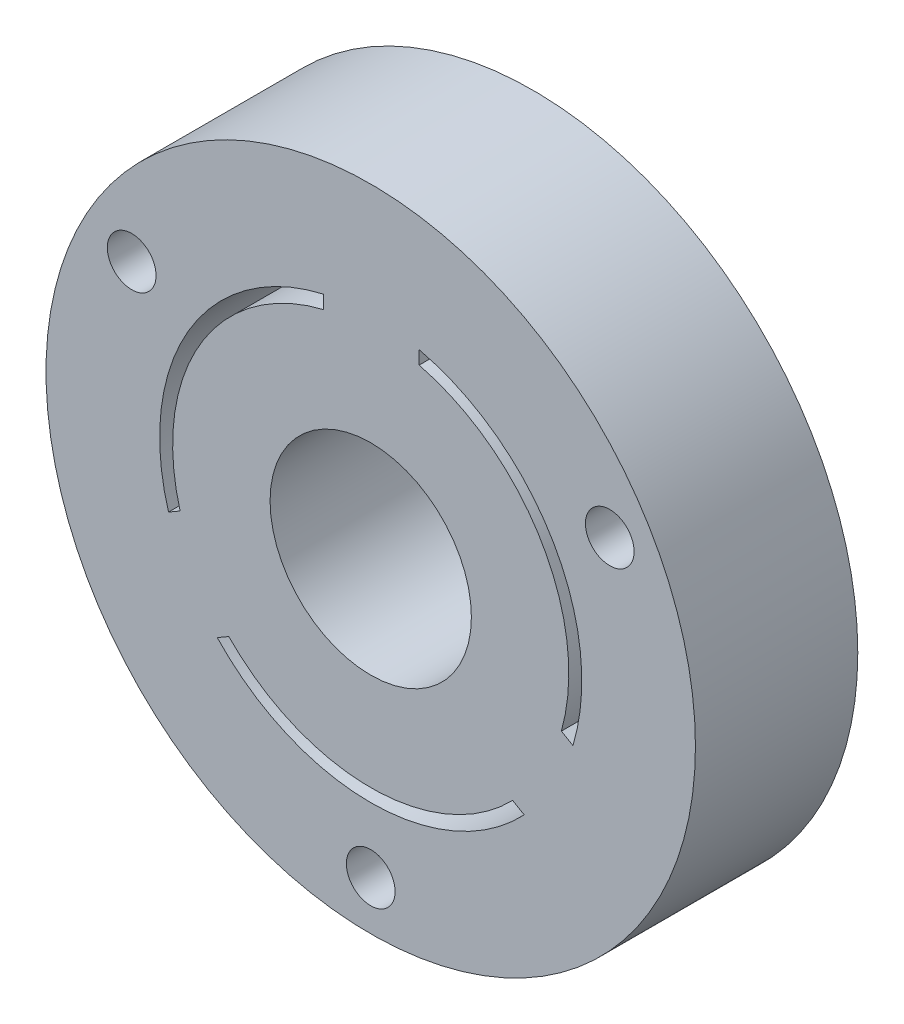
SolidWorks part; units mm, degrees
ref_plane "前视基准面" through (0, 0, 0) normal (0, 0, 1) x (1, 0, 0)
ref_plane "上视基准面" through (0, 0, 0) normal (0, 1, 0) x (1, 0, 0)
ref_plane "右视基准面" through (0, 0, 0) normal (1, 0, 0) x (0, 0, -1)
sketch "草图1" plane through (0, 0, 0) normal (0, 0, 1) x (1, 0, 0)
  line L0 (48.2965, 27.9249) -> (48.2965, 37.9249) construction
  line L1 (48.2965, 27.9249) -> (39.6362, 22.9249) construction
  line L2 (48.2965, 27.9249) -> (74.2772, 12.9249) construction
  line L3 (81.0732, 9.0013) -> (81.8232, 10.3003)
  line L7 (46.8483, 66.0915) -> (46.8483, 32.6388)
  line L11 (49.7879, 66.0915) -> (49.7879, 32.6388)
  line L12 (81.0732, 9.0013) -> (80.3232, 7.7022)
  line L13 (81.8232, 10.3003) -> (52.5654, 27.1923)
  line L14 (52.5654, 27.1923) -> (51.0654, 24.5942)
  line L15 (51.0654, 24.5942) -> (80.3232, 7.7022)
  line L16 (15.5198, 9.0013) -> (14.7698, 10.3003)
  line L17 (15.5198, 9.0013) -> (16.2698, 7.7022)
  line L18 (14.7698, 10.3003) -> (43.9274, 27.1345)
  line L19 (43.9274, 27.1345) -> (45.4274, 24.5364)
  line L20 (45.4274, 24.5364) -> (16.2698, 7.7022)
  line L21 (46.8483, 32.6388) -> (49.7879, 32.6388)
  line L22 (46.8483, 66.0915) -> (49.7879, 66.0915)
  circle A1 centre (48.2965, 27.9249) radius 3.1
  circle A2 centre (48.2965, 27.9249) radius 6.1
  circle A3 centre (48.2965, 27.9249) radius 10
  circle A4 centre (48.2965, 27.9249) radius 6.5
  dimension "D1" = 3
  dimension "D2" = 3.5
extrude "凸台-拉伸2" add sketch "草图1" along normal blind 5 contours A4 L7 A3 L18 | A4 L13 A3 L11 | A4 L20 A3 L15 | A4 L18 A3 L20 | L18 A4 L20 A2 | L7 A2 L18 L19 L20 L15 L14 L13 L11 L21 A1 | L18 A2 L20 L19 | L15 A2 L13 L14 | L11 A2 L7 L21 | L11 A4 L7 A2 | L15 A4 L13 A2 | A4 L15 A3 L13 | A4 L11 A3 L7
sketch "草图2" plane through (0, 0, 5) normal (0, 0, 1) x (1, 0, 0)
  line L0 (48.2965, 27.9249) -> (40.9353, 32.1749)
  line L1 (48.2965, 27.9249) -> (55.6577, 32.1749)
  line L2 (48.2965, 27.9249) -> (48.2965, 19.4249)
  circle A0 centre (40.9353, 32.1749) radius 0.75
  circle A1 centre (55.6577, 32.1749) radius 0.75
  circle A2 centre (48.2965, 19.4249) radius 0.75
extrude "切除-拉伸1" cut sketch "草图2" against normal blind 5
